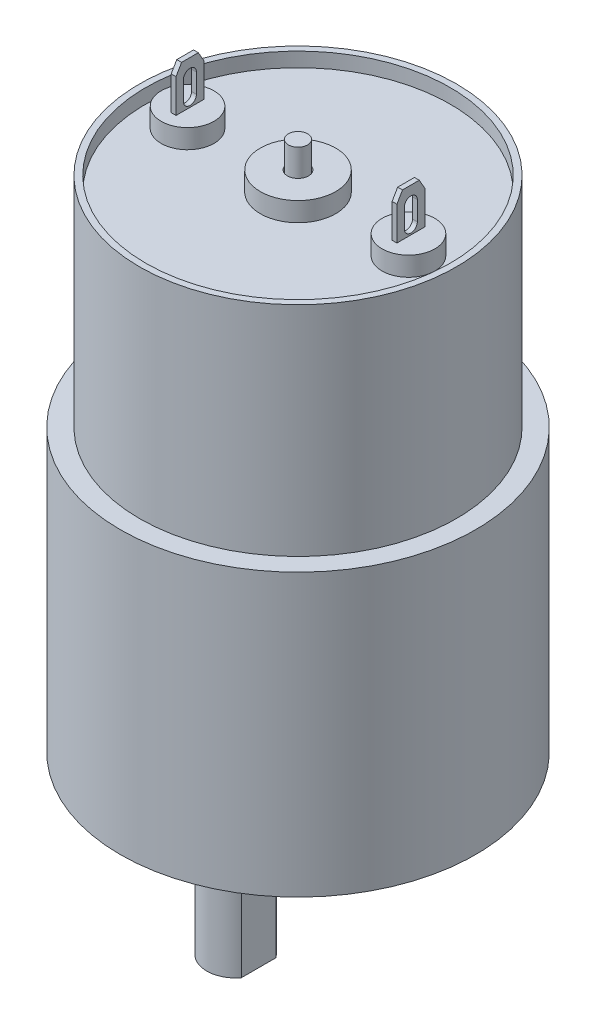
SolidWorks part; units mm, degrees
ref_plane "Front Plane" through (0, 0, 0) normal (0, 0, 1) x (1, 0, 0)
ref_plane "Top Plane" through (0, 0, 0) normal (0, 1, 0) x (1, 0, 0)
ref_plane "Right Plane" through (0, 0, 0) normal (1, 0, 0) x (0, 0, -1)
sketch "Schizzo1" plane through (0, 0, 0) normal (0, 1, 0) x (1, 0, 0)
  circle A0 centre (0, 0) radius 18.5
  dimension "D1" = 37
extrude "Estrusione-Estrusione1" add sketch "Schizzo1" along normal blind 29.3
sketch "Schizzo2" plane through (0, 29.3, 0) normal (0, 1, 0) x (1, 0, 0)
  circle A0 centre (0, 0) radius 16.5
  dimension "D1" = 33
extrude "Estrusione-Estrusione2" add sketch "Schizzo2" along normal blind 22.7
sketch "Schizzo3" plane through (0, 52, 0) normal (0, 1, 0) x (1, 0, 0)
  circle A0 centre (0, 0) radius 16.5 construction
  circle A1 centre (0, 0) radius 16.5
  circle A2 centre (0, 0) radius 15.85
  dimension "D1" = 0.65
extrude "Taglio-Estrusione1" cut sketch "Schizzo3" against normal blind 1.5 contours A2
sketch "Schizzo4" plane through (0, 50.5, 0) normal (0, 1, 0) x (1, 0, 0)
  line L0 (-11.5, 0) -> (11.5, 0) construction
  circle A0 centre (11.5, 0) radius 2.75
  circle A1 centre (-11.5, 0) radius 2.75
  circle A2 centre (0, 0) radius 3.925
  point P4 (0, 0)
  dimension "D2" = 5.5
  dimension "D3" = 7.85
  dimension "D1" = 23
extrude "Estrusione-Estrusione3" add sketch "Schizzo4" along normal blind 2
sketch "Schizzo5" plane through (0, 52.5, 0) normal (0, 1, 0) x (1, 0, 0)
  line L1 (-11.75, -1.45) -> (-11.25, -1.45)
  line L2 (-11.75, -1.45) -> (-11.75, 1.45)
  line L3 (-11.75, 1.45) -> (-11.25, 1.45)
  line L4 (-11.25, -1.45) -> (-11.25, 1.45)
  line L5 (-11.75, -1.45) -> (-11.25, 1.45) construction
  line L6 (-11.75, 1.45) -> (-11.25, -1.45) construction
  line L7 (11.25, -1.45) -> (11.75, -1.45)
  line L8 (11.25, -1.45) -> (11.25, 1.45)
  line L9 (11.25, 1.45) -> (11.75, 1.45)
  line L10 (11.75, -1.45) -> (11.75, 1.45)
  line L11 (11.25, -1.45) -> (11.75, 1.45) construction
  line L12 (11.25, 1.45) -> (11.75, -1.45) construction
  circle A1 centre (11.5, 0) radius 2.75
  circle A2 centre (11.5, 0) radius 2.75 construction
  circle A3 centre (-11.5, 0) radius 2.75
  circle A4 centre (-11.5, 0) radius 2.75 construction
  dimension "D3" = 0.5
  dimension "D4" = 0.5
  dimension "D5" = 2.9
  dimension "D1" = 0
  dimension "D2" = 0
extrude "Estrusione-Estrusione4" add sketch "Schizzo5" along normal blind 4.5
chamfer "Smusso1" distance 1 angle 30 4 edges at (11.5, 57, 1.45) (11.5, 57, -1.45) (-11.5, 57, -1.45) (-11.5, 57, 1.45)
sketch "Schizzo6" plane through (-11.75, 0, 0) normal (-1, 0, 0) x (0, 0, 1)
  line L0 (0, 55.35) -> (0, 53.35) construction
  line L1 (0.675, 55.35) -> (0.675, 53.35)
  line L2 (-0.675, 55.35) -> (-0.675, 53.35)
  line L5 (-1.45, 52.5) -> (1.45, 52.5) construction
  arc A0 (0.675, 55.35) -> (-0.675, 55.35) centre (0, 55.35) ccw
  arc A1 (-0.675, 53.35) -> (0.675, 53.35) centre (0, 53.35) ccw
  point P3 (0, 54.35)
  dimension "D2" = 0.85
  dimension "D3" = 1.35
  dimension "D1" = 2
extrude "Taglio-Estrusione2" cut sketch "Schizzo6" against normal through all
sketch "Schizzo7" plane through (0, 52.5, 0) normal (0, 1, 0) x (1, 0, 0)
  circle A0 centre (0, 0) radius 1.1
  dimension "D1" = 2.2
extrude "Taglio-Estrusione3" cut sketch "Schizzo7" against normal up to surface (2 mm away) up to face at (0, 50.5, 3.925)
sketch "Schizzo8" plane through (0, 50.5, 0) normal (0, 1, 0) x (1, 0, 0)
  circle A0 centre (0, 0) radius 1
  dimension "D1" = 2
extrude "Estrusione-Estrusione5" add sketch "Schizzo8" along normal blind 4.75
sketch "Schizzo9" plane through (0, 0, 0) normal (0, -1, 0) x (1, 0, 0)
  circle A0 centre (0, 0) radius 15.5 construction
  circle A1 centre (0, -15.5) radius 1.5
  circle A2 centre (-13.4234, -7.75) radius 1.5
  circle A3 centre (-13.4234, 7.75) radius 1.5
  circle A4 centre (0, 15.5) radius 1.5
  circle A5 centre (13.4234, 7.75) radius 1.5
  circle A6 centre (13.4234, -7.75) radius 1.5
  dimension "D1" = 31
  dimension "D2" = 3
  dimension "D3" = 6
extrude "Taglio-Estrusione4" cut sketch "Schizzo9" against normal blind 5
sketch "Schizzo10" plane through (0, 0, 0) normal (0, -1, 0) x (1, 0, 0)
  line L0 (-12.5, 0) -> (18.5, 0) construction
  circle A1 centre (-6.5, 0) radius 6
  circle A2 centre (0, 0) radius 18.5 construction
  dimension "D1" = 12
  dimension "D2" = 31
extrude "Estrusione-Estrusione6" add sketch "Schizzo10" along normal blind 6
sketch "Schizzo11" plane through (0, -6, 0) normal (0, -1, 0) x (1, 0, 0)
  circle A0 centre (-6.5, 0) radius 3
  dimension "D1" = 6
extrude "Estrusione-Estrusione7" add sketch "Schizzo11" along normal blind 3.5
sketch "Schizzo12" plane through (0, -9.5, 0) normal (0, -1, 0) x (1, 0, 0)
  line L0 (-4.1, -1.8) -> (-4.1, 1.8)
  line L1 (-4.1, 0) -> (-9.5, 0) construction
  circle A1 centre (-6.5, 0) radius 3
  arc A2 (-4.1, 1.8) -> (-4.1, -1.8) centre (-6.5, 0) ccw
  circle M4 centre (-6.5, 0) radius 3
  dimension "D1" = 0
extrude "Estrusione-Estrusione8" add sketch "Schizzo12" along normal blind 12 contours L0 L1 A2 | L1 L0 M4
sketch "Croquis1" plane through (0, 0, 0) normal (0, -1, 0) x (1, 0, 0)
  circle A0 centre (-15.5, 0) radius 2
  arc A1 (-13.4234, 7.75) -> (-13.4234, -7.75) centre (0, 0) ccw construction
  arc A2 (13.4234, 7.75) -> (0, 15.5) centre (0, 0) ccw construction
  arc A4 (13.4234, -7.75) -> (0, -15.5) centre (0, 0) cw construction
  circle A5 centre (7.75, 13.4234) radius 2
  circle A6 centre (7.75, -13.4234) radius 2
  point P8 (-13.4234, -7.75)
  dimension "D1" = 4
extrude "Cortar-Extruir1" cut sketch "Croquis1" against normal blind 10 contours A6 | A0 | A5
